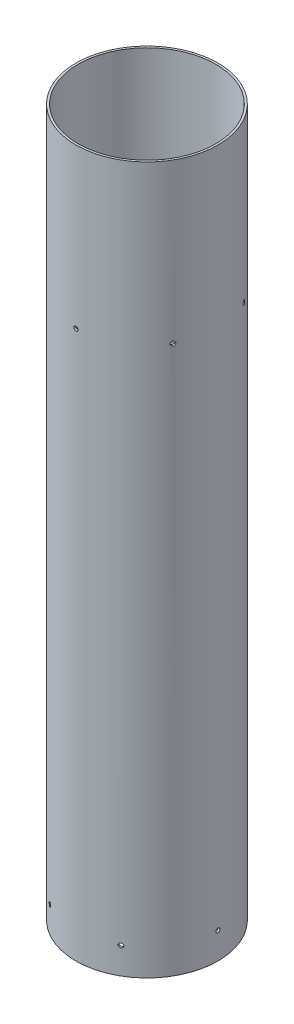
SolidWorks part; units mm, degrees
ref_plane "Front Plane" through (0, 0, 0) normal (0, 0, 1) x (1, 0, 0)
ref_plane "Top Plane" through (0, 0, 0) normal (0, 1, 0) x (1, 0, 0)
ref_plane "Right Plane" through (0, 0, 0) normal (1, 0, 0) x (0, 0, -1)
sketch "Sketch2" plane through (0, 0, 0) normal (0, 1, 0) x (1, 0, 0)
  circle A0 centre (0, 0) radius 51.054
  circle A1 centre (0, 0) radius 49.53
  dimension "D1" = 102.108
  dimension "D2" = 99.06
extrude "Boss-Extrude1" add sketch "Sketch2" along normal blind 508
sketch "Sketch3" plane through (0, 0, 0) normal (0, 0, 1) x (1, 0, 0)
  line L0 (0, 508) -> (0, 395.224)
  line L1 (49.53, 508) -> (-49.53, 508) construction
  line L2 (0, 395.224) -> (0, 393.7)
  circle A0 centre (0, 393.7) radius 1.524
  dimension "D2" = 3.048
  dimension "D1" = 112.776
extrude "Cut-Extrude1" cut sketch "Sketch3" against normal blind 74.422
pattern_circular "CirPattern1" count 6 over 360 about axis through (0, 508, 0) along (0, -1, 0) of "Cut-Extrude1"
sketch "Sketch4" plane through (0, 0, 0) normal (1, 0, 0) x (0, 0, -1)
  line L0 (0, 0) -> (0, 17.526) construction
  line L1 (-51.054, 0) -> (51.054, 0) construction
  line L2 (0, 17.526) -> (0, 19.05) construction
  circle A0 centre (0, 19.05) radius 1.524
  dimension "D2" = 3.048
  dimension "D1" = 17.526
extrude "Cut-Extrude2" cut sketch "Sketch4" against normal blind 74.422
pattern_circular "CirPattern2" count 6 over 360 about axis through (0, 508, 0) along (0, -1, 0) of "Cut-Extrude2"
